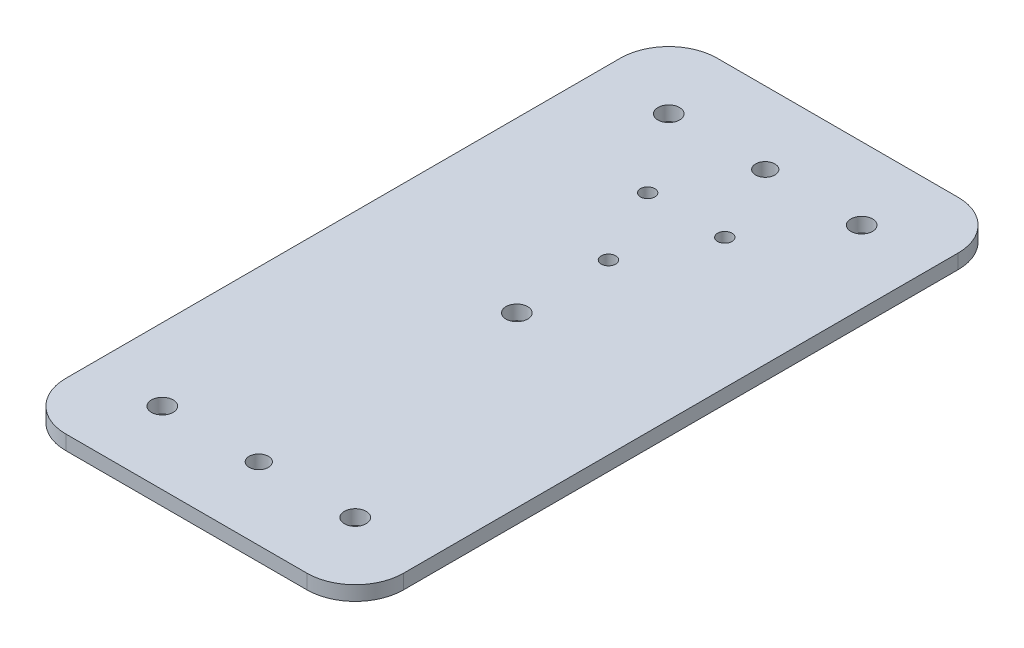
SolidWorks part; units mm, degrees
ref_plane "前视基准面" through (0, 0, 0) normal (0, 0, 1) x (1, 0, 0)
ref_plane "上视基准面" through (0, 0, 0) normal (0, 1, 0) x (1, 0, 0)
ref_plane "右视基准面" through (0, 0, 0) normal (1, 0, 0) x (0, 0, -1)
other "Configuration Table"
sketch "草图1" plane through (0, 0, 0) normal (0, 1, 0) x (1, 0, 0)
  line L1 (0, 0) -> (70, 0)
  line L2 (0, 0) -> (0, -135)
  line L3 (0, -135) -> (70, -135)
  line L4 (70, 0) -> (70, -135)
  dimension "D1" = 70
  dimension "D2" = 135
extrude "凸台-拉伸1" add sketch "草图1" along normal blind 3
sketch "草图2" plane through (0, 3, 0) normal (0, 1, 0) x (1, 0, 0)
  line L0 (15, 3.842) -> (15, -124.6321) construction
  line L1 (55, 3.842) -> (55, -135) construction
  line L2 (0, -135) -> (70, -135) construction
  line L3 (0, 0) -> (0, -135) construction
  line L4 (70, -135) -> (70, 0) construction
  line L5 (-29.316, -15) -> (79.0889, -15) construction
  line L6 (-26.4716, -120) -> (101.2123, -120) construction
  line L7 (70, 0) -> (0, 0) construction
  line L8 (35, 6.2634) -> (35, -129.5913) construction
  circle A0 centre (15, -15) radius 2.25
  circle A1 centre (55, -15) radius 2.25
  circle A2 centre (15, -120) radius 2.25
  circle A3 centre (55, -120) radius 2.25
  circle A4 centre (35, -120) radius 2
  circle A5 centre (35, -15) radius 2
  dimension "D5" = 4.5
  dimension "D6" = 4.5
  dimension "D7" = 4.5
  dimension "D8" = 4.5
  dimension "D2" = 4
  dimension "D9" = 4
  dimension "D1" = 15
  dimension "15" = 15
  dimension "D3" = 15
  dimension "D4" = 15
extrude "切除-拉伸1" cut sketch "草图2" against normal through all
fillet "圆角1" radius 10 4 edges at (70, 1.5, 135) (0, 1.5, 135) (0, 1.5, 0) (70, 1.5, 0)
sketch "草图3" plane through (0, 0, 0) normal (0, -1, 0) x (1, 0, 0)
  line L0 (35, 135) -> (35, 41.9028) construction
  line L1 (10, 135) -> (60, 135) construction
  line L2 (-37.436, 66.5) -> (84.5919, 66.5) construction
  circle A0 centre (35, 47.5) radius 1.5
  circle A1 centre (43, 31.3755) radius 1.5
  circle A2 centre (27, 31.3755) radius 1.5
  circle A3 centre (35, 66.5) radius 2.25
  dimension "D1" = 3
  dimension "D2" = 3
  dimension "D3" = 3
  dimension "D5" = 4.5
  dimension "D4" = 19
extrude "切除-拉伸2" cut sketch "草图3" against normal through all
